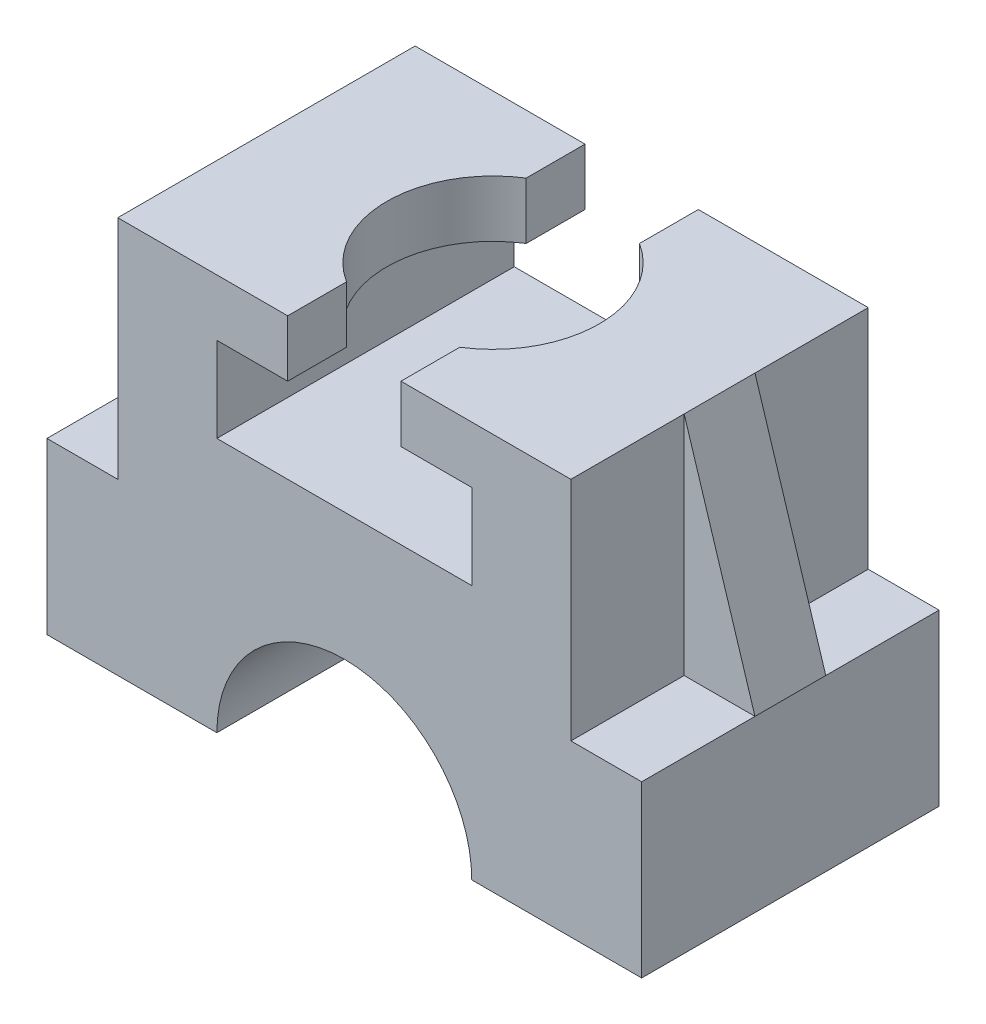
SolidWorks part; units mm, degrees
ref_plane "Front Plane" through (0, 0, 0) normal (0, 0, 1) x (1, 0, 0)
ref_plane "Top Plane" through (0, 0, 0) normal (0, 1, 0) x (1, 0, 0)
ref_plane "Right Plane" through (0, 0, 0) normal (1, 0, 0) x (0, 0, -1)
sketch "Sketch1" plane through (0, 0, 0) normal (0, 0, 1) x (1, 0, 0)
  line L0 (-105, 0) -> (-45, 0)
  line L1 (0, 0) -> (0, 120.4234) construction
  line L2 (105, 0) -> (45, 0)
  line L3 (-105, 0) -> (-105, 60)
  line L4 (-105, 60) -> (-80, 60)
  line L5 (-80, 60) -> (-80, 140)
  line L6 (-80, 140) -> (-20, 140)
  line L7 (-20, 140) -> (-20, 120)
  line L8 (-20, 120) -> (-45, 120)
  line L9 (-45, 120) -> (-45, 90)
  line L10 (-45, 90) -> (45, 90)
  line L11 (105, 0) -> (105, 60)
  line L12 (105, 60) -> (80, 60)
  line L13 (45, 120) -> (45, 90)
  line L14 (20, 120) -> (45, 120)
  line L15 (20, 140) -> (20, 120)
  line L16 (80, 140) -> (20, 140)
  line L17 (80, 60) -> (80, 140)
  arc A0 (45, 0) -> (-45, 0) centre (0, 0) ccw
  point P18 (0, 90)
  dimension "D2" = 90
  dimension "D1" = 60
  dimension "D3" = 60
  dimension "D4" = 80
  dimension "D5" = 40
  dimension "D6" = 30
  dimension "D7" = 90
  dimension "D8" = 60
  dimension "D9" = 50
extrude "Boss-Extrude1" add sketch "Sketch1" against normal mid plane 105
sketch "Sketch2" plane through (0, 0, 0) normal (0, 0, 1) x (1, 0, 0)
  line L0 (80, 140) -> (80, 60)
  line L1 (80, 60) -> (80, 140) construction
  line L2 (80, 60) -> (105, 60)
  line L3 (105, 60) -> (80, 60) construction
  line L4 (105, 60) -> (80, 140)
  line L5 (0, 0) -> (0, 119.8797) construction
  line L6 (-105, 60) -> (-80, 140)
  line L7 (-80, 60) -> (-105, 60)
  line L8 (-80, 140) -> (-80, 60)
  dimension "D1" = 25
  dimension "D2" = 80
extrude "Boss-Extrude2" add sketch "Sketch2" along normal mid plane 25
sketch "Sketch3" plane through (0, 140, 0) normal (0, 1, 0) x (1, 0, 0)
  circle A0 centre (0, 0) radius 37.5
  dimension "D1" = 75
extrude "Cut-Extrude1" cut sketch "Sketch3" against normal up to surface (20 mm away) up to face at (-32.5, 120, 0)
